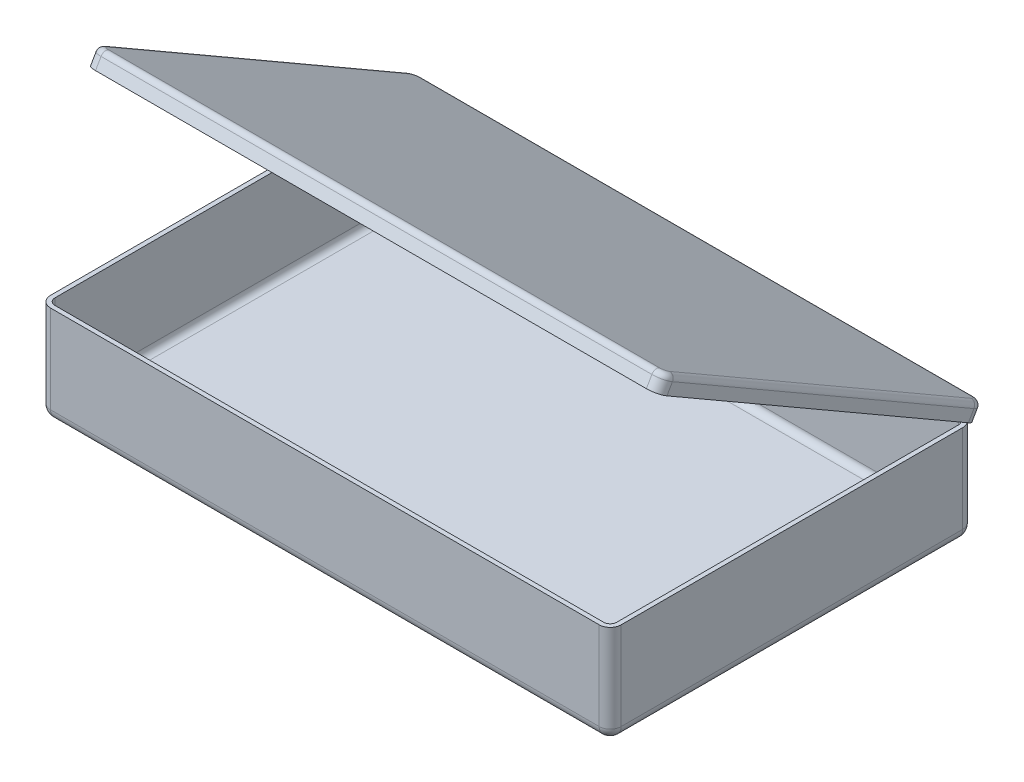
SolidWorks part; units mm, degrees
material "Acrylic (Medium-high impact)"
ref_plane "Front" through (0, 0, 0) normal (0, 0, 1) x (1, 0, 0)
ref_plane "Top" through (0, 0, 0) normal (0, 1, 0) x (1, 0, 0)
ref_plane "Right" through (0, 0, 0) normal (1, 0, 0) x (0, 0, -1)
sketch "Sketch1" plane through (0, 0, 0) normal (0, 1, 0) x (1, 0, 0)
  line L1 (-164.465, 104.775) -> (164.465, 104.775)
  line L2 (-164.465, 104.775) -> (-164.465, -104.775)
  line L3 (-164.465, -104.775) -> (164.465, -104.775)
  line L4 (164.465, 104.775) -> (164.465, -104.775)
  line L5 (-164.465, 104.775) -> (164.465, -104.775) construction
  line L6 (-164.465, -104.775) -> (164.465, 104.775) construction
  point P0 (0, 0)
  dimension "D1" = 328.93
  dimension "D2" = 209.55
extrude "Boss-Extrude1" add sketch "Sketch1" along normal blind 57.15
fillet "Fillet1" radius 6.35 8 edges at (0, 0, -104.775) (-164.465, 0, 0) (0, 0, 104.775) (164.465, 0, 0) (-164.465, 28.575, -104.775) (164.465, 28.575, -104.775) (164.465, 28.575, 104.775) (-164.465, 28.575, 104.775)
shell "Shell1" thickness 2.54
sketch "Sketch2" plane through (0, 0, 0) normal (1, 0, 0) x (0, 0, -1)
  line L0 (104.775, 57.15) -> (106.5711, 55.3539) construction
  line L2 (106.5711, 55.3539) -> (-78.2041, 162.0339)
  line L3 (-78.2041, 162.0339) -> (-73.4416, 170.2828)
  line L4 (-73.4416, 170.2828) -> (111.3336, 63.6028)
  line L5 (106.5711, 55.3539) -> (111.3336, 63.6028)
  line L6 (104.775, 57.15) -> (104.775, 55.3539) construction
  line L7 (104.775, 55.3539) -> (106.5711, 55.3539) construction
  line L8 (-98.425, 57.15) -> (98.425, 57.15) construction
  dimension "D1" = 2.54
  dimension "D2" = 9.525
  dimension "D3" = 213.36
  dimension "D4" = 30
extrude "LID OPENING ANGLE CONTROL" add sketch "Sketch2" along normal mid plane 330.2 separate body
fillet "Fillet2" radius 6.35 4 edges at (165.1, 59.4784, -108.9523) (-165.1, 59.4784, -108.9523) (165.1, 166.1584, 75.8229) (-165.1, 166.1584, 75.8229)
fillet "Fillet3" radius 3.175 8 edges at (163.2401, 169.3529, 71.8309) (0, 170.2828, 73.4416) (-163.2401, 169.3529, 71.8309) (-165.1, 116.9428, -18.946) (-163.2401, 64.5328, -109.7229) (0, 63.6028, -111.3336) (163.2401, 64.5328, -109.7229) (165.1, 116.9428, -18.946)
shell "Shell2" thickness 2.54
